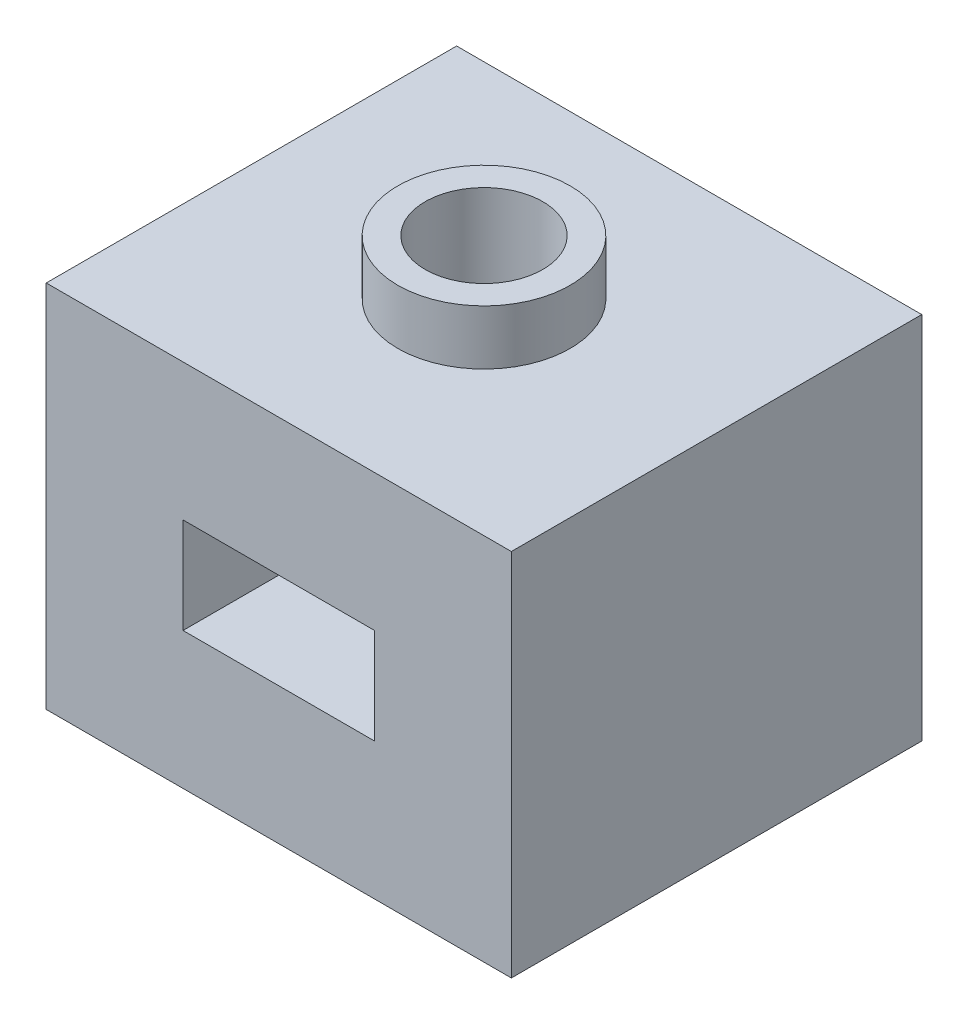
SolidWorks part; units mm, degrees
ref_plane "Front Plane" through (0, 0, 0) normal (0, 0, 1) x (1, 0, 0)
ref_plane "Top Plane" through (0, 0, 0) normal (0, 1, 0) x (1, 0, 0)
ref_plane "Right Plane" through (0, 0, 0) normal (1, 0, 0) x (0, 0, -1)
sketch "Sketch2" plane through (0, 0, 0) normal (0, 0, 1) x (1, 0, 0)
  line L0 (-8.5, 6.75) -> (-8.5, -6.75)
  line L1 (-3.5, 1.75) -> (3.5, 1.75)
  line L2 (-3.5, 1.75) -> (-3.5, -1.75)
  line L3 (-3.5, -1.75) -> (3.5, -1.75)
  line L4 (3.5, 1.75) -> (3.5, -1.75)
  line L5 (-3.5, 1.75) -> (3.5, -1.75) construction
  line L6 (-3.5, -1.75) -> (3.5, 1.75) construction
  line L7 (-8.5, -6.75) -> (8.5, -6.75)
  line L8 (8.5, 6.75) -> (8.5, -6.75)
  line L9 (-8.5, 6.75) -> (8.5, 6.75)
  point P0 (0, 0)
  dimension "D1" = 7
  dimension "D2" = 3.5
  dimension "D3" = 5
extrude "Boss-Extrude1" add sketch "Sketch2" along normal blind 15
sketch "Sketch3" plane through (0, 6.75, 0) normal (0, 1, 0) x (1, 0, 0)
  circle A0 centre (0, -7.5) radius 2.15
  dimension "D1" = 4.3
extrude "Cut-Extrude1" cut sketch "Sketch3" against normal blind 15
sketch "Sketch4" plane through (0, 6.75, 0) normal (0, 1, 0) x (1, 0, 0)
  line L4 (8.5, 0) -> (-8.5, 0)
  line L5 (-8.5, 0) -> (-8.5, -15)
  line L6 (-8.5, -15) -> (8.5, -15)
  line L7 (8.5, -15) -> (8.5, 0)
  line L8 (8.5, 0) -> (-8.5, 0)
  line L9 (-8.5, 0) -> (-8.5, -15)
  line L10 (-8.5, -15) -> (8.5, -15)
  line L11 (8.5, -15) -> (8.5, 0)
  circle A0 centre (0, -7.5) radius 2.15 construction
  circle A1 centre (0, -7.5) radius 2.15
  circle A2 centre (0, -7.5) radius 3.15
  circle M6 centre (0, -7.5) radius 2.15
  dimension "D1" = 0
  dimension "D2" = 1
extrude "Boss-Extrude2" add sketch "Sketch4" along normal blind 2 contours A2 M6
